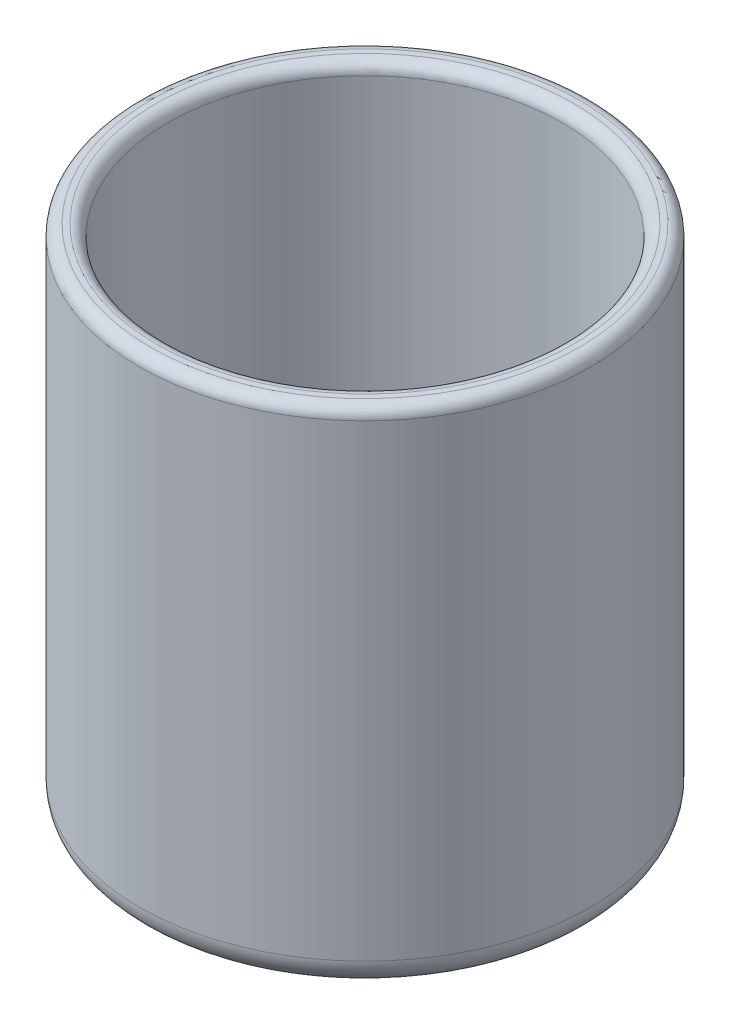
SolidWorks part; units mm, degrees
ref_plane "Front Plane" through (0, 0, 0) normal (0, 0, 1) x (1, 0, 0)
ref_plane "Top Plane" through (0, 0, 0) normal (0, 1, 0) x (1, 0, 0)
ref_plane "Right Plane" through (0, 0, 0) normal (1, 0, 0) x (0, 0, -1)
sketch "Sketch1" plane through (0, 0, 0) normal (0, 1, 0) x (1, 0, 0)
  circle A0 centre (0, 0) radius 40
  dimension "D1" = 80
extrude "Boss-Extrude1" add sketch "Sketch1" along normal blind 90 contours A0
sketch "Sketch2" plane through (0, 90, 0) normal (0, 1, 0) x (1, 0, 0)
  circle A0 centre (0, 0) radius 35
  dimension "D1" = 70
extrude "Cut-Extrude1" cut sketch "Sketch2" against normal blind 85
fillet "Fillet1" radius 2 2 edges at (0, 90, 40) (0, 90, 35)
fillet "Fillet2" radius 5 2 edges at (0, 5, 35) (0, 0, 40)
